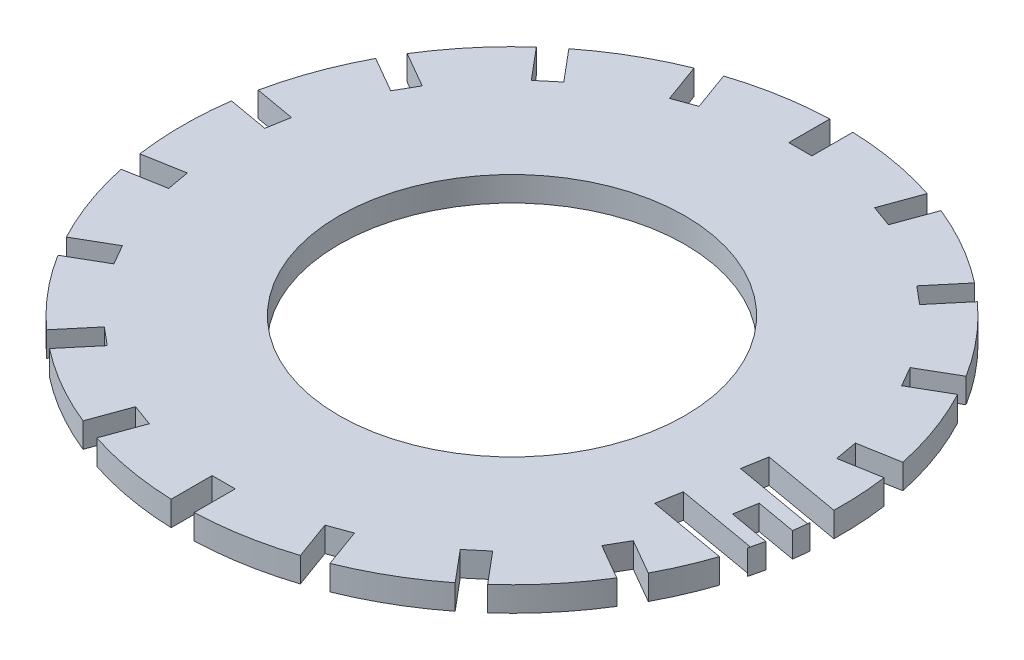
SolidWorks part; units mm, degrees
ref_plane "Plan de face" through (0, 0, 0) normal (0, 0, 1) x (1, 0, 0)
ref_plane "Plan de dessus" through (0, 0, 0) normal (0, 1, 0) x (1, 0, 0)
ref_plane "Plan de droite" through (0, 0, 0) normal (1, 0, 0) x (0, 0, -1)
sketch "Esquisse1" plane through (0, 0, 0) normal (0, 1, 0) x (1, 0, 0)
  line L0 (0, 0) -> (0, 40) construction
  line L1 (0, 40) -> (8.5644, 40) construction
  circle A0 centre (0, 0) radius 40
  circle A1 centre (0, 0) radius 21
  dimension "D1" = 80
  dimension "D2" = 42
extrude "Boss.-Extru.1" add sketch "Esquisse1" along normal blind 3
sketch "Esquisse2" plane through (0, 3, 0) normal (0, 1, 0) x (1, 0, 0)
  line L0 (0, 0) -> (0, 40) construction
  line L1 (0, 40) -> (2.8, 40) construction
  line L2 (14.9964, 37.1089) -> (13.2863, 32.4104)
  line L3 (1.4, 40) -> (-1.4, 40)
  line L4 (1.4, 40) -> (1.4, 35)
  line L5 (1.4, 35) -> (-1.4, 35)
  line L6 (-1.4, 40) -> (-1.4, 35)
  line L7 (14.9964, 37.1089) -> (12.3652, 38.0665)
  line L8 (12.3652, 38.0665) -> (10.6551, 33.3681)
  line L9 (13.2863, 32.4104) -> (10.6551, 33.3681)
  line L10 (26.784, 29.7419) -> (23.57, 25.9117)
  line L11 (26.784, 29.7419) -> (24.639, 31.5417)
  line L12 (24.639, 31.5417) -> (21.4251, 27.7115)
  line L13 (23.57, 25.9117) -> (21.4251, 27.7115)
  line L14 (35.341, 18.7876) -> (31.0109, 16.2876)
  line L15 (35.341, 18.7876) -> (33.941, 21.2124)
  line L16 (33.941, 21.2124) -> (29.6109, 18.7124)
  line L17 (31.0109, 16.2876) -> (29.6109, 18.7124)
  line L18 (39.6354, 5.5672) -> (34.7114, 4.699)
  line L19 (39.6354, 5.5672) -> (39.1492, 8.3247)
  line L20 (39.1492, 8.3247) -> (34.2252, 7.4564)
  line L21 (34.7114, 4.699) -> (34.2252, 7.4564)
  line L22 (39.1492, -8.3247) -> (34.2252, -7.4564)
  line L23 (39.1492, -8.3247) -> (39.6354, -5.5672)
  line L24 (39.6354, -5.5672) -> (34.7114, -4.699)
  line L25 (34.2252, -7.4564) -> (34.7114, -4.699)
  line L26 (33.941, -21.2124) -> (29.6109, -18.7124)
  line L27 (33.941, -21.2124) -> (35.341, -18.7876)
  line L28 (35.341, -18.7876) -> (31.0109, -16.2876)
  line L29 (29.6109, -18.7124) -> (31.0109, -16.2876)
  line L30 (24.639, -31.5417) -> (21.4251, -27.7115)
  line L31 (24.639, -31.5417) -> (26.784, -29.7419)
  line L32 (26.784, -29.7419) -> (23.57, -25.9117)
  line L33 (21.4251, -27.7115) -> (23.57, -25.9117)
  line L34 (12.3652, -38.0665) -> (10.6551, -33.3681)
  line L35 (12.3652, -38.0665) -> (14.9964, -37.1089)
  line L36 (14.9964, -37.1089) -> (13.2863, -32.4104)
  line L37 (10.6551, -33.3681) -> (13.2863, -32.4104)
  line L38 (-1.4, -40) -> (-1.4, -35)
  line L39 (-1.4, -40) -> (1.4, -40)
  line L40 (1.4, -40) -> (1.4, -35)
  line L41 (-1.4, -35) -> (1.4, -35)
  line L42 (-14.9964, -37.1089) -> (-13.2863, -32.4104)
  line L43 (-14.9964, -37.1089) -> (-12.3652, -38.0665)
  line L44 (-12.3652, -38.0665) -> (-10.6551, -33.3681)
  line L45 (-13.2863, -32.4104) -> (-10.6551, -33.3681)
  line L46 (-26.784, -29.7419) -> (-23.57, -25.9117)
  line L47 (-26.784, -29.7419) -> (-24.639, -31.5417)
  line L48 (-24.639, -31.5417) -> (-21.4251, -27.7115)
  line L49 (-23.57, -25.9117) -> (-21.4251, -27.7115)
  line L50 (-35.341, -18.7876) -> (-31.0109, -16.2876)
  line L51 (-35.341, -18.7876) -> (-33.941, -21.2124)
  line L52 (-33.941, -21.2124) -> (-29.6109, -18.7124)
  line L53 (-31.0109, -16.2876) -> (-29.6109, -18.7124)
  line L54 (-39.6354, -5.5672) -> (-34.7114, -4.699)
  line L55 (-39.6354, -5.5672) -> (-39.1492, -8.3247)
  line L56 (-39.1492, -8.3247) -> (-34.2252, -7.4564)
  line L57 (-34.7114, -4.699) -> (-34.2252, -7.4564)
  line L58 (-39.1492, 8.3247) -> (-34.2252, 7.4564)
  line L59 (-39.1492, 8.3247) -> (-39.6354, 5.5672)
  line L60 (-39.6354, 5.5672) -> (-34.7114, 4.699)
  line L61 (-34.2252, 7.4564) -> (-34.7114, 4.699)
  line L62 (-33.941, 21.2124) -> (-29.6109, 18.7124)
  line L63 (-33.941, 21.2124) -> (-35.341, 18.7876)
  line L64 (-35.341, 18.7876) -> (-31.0109, 16.2876)
  line L65 (-29.6109, 18.7124) -> (-31.0109, 16.2876)
  line L66 (-24.639, 31.5417) -> (-21.4251, 27.7115)
  line L67 (-24.639, 31.5417) -> (-26.784, 29.7419)
  line L68 (-26.784, 29.7419) -> (-23.57, 25.9117)
  line L69 (-21.4251, 27.7115) -> (-23.57, 25.9117)
  line L70 (-12.3652, 38.0665) -> (-10.6551, 33.3681)
  line L71 (-12.3652, 38.0665) -> (-14.9964, 37.1089)
  line L72 (-14.9964, 37.1089) -> (-13.2863, 32.4104)
  line L73 (-10.6551, 33.3681) -> (-13.2863, 32.4104)
  circle A0 centre (0, 0) radius 40 construction
  point P81 (0, 0)
  dimension "D1" = 2.8
  dimension "D2" = 1.4
  dimension "D3" = 5
  dimension "D4" = 18
extrude "Enlèv. mat.-Extru.1" cut sketch "Esquisse2" against normal up to next
sketch "Esquisse3" plane through (0, 3, 0) normal (0, 1, 0) x (1, 0, 0)
  line L0 (0, 0) -> (84.8474, -14.8594) construction
  line L1 (84.587, -16.3366) -> (85.1079, -13.3821) construction
  line L10 (30.7507, 2.4571) -> (27.677, -15.0937) construction
  line L19 (30.4531, 0.7581) -> (29.9356, -2.197)
  line L24 (30.4531, 0.7581) -> (40.3032, -0.967)
  line L25 (29.9356, -2.197) -> (39.7857, -3.922)
  line L26 (40.3032, -0.967) -> (39.7857, -3.922)
  line L27 (28.3831, -11.0621) -> (28.9006, -8.107)
  line L28 (28.3831, -11.0621) -> (38.2332, -12.7871)
  line L29 (28.9006, -8.107) -> (38.7507, -9.8321)
  line L30 (38.2332, -12.7871) -> (38.7507, -9.8321)
  dimension "D1" = 3
  dimension "D2" = 10
  dimension "D3" = 6
  dimension "D4" = 3
extrude "Enlèv. mat.-Extru.2" cut sketch "Esquisse3" against normal blind 10
